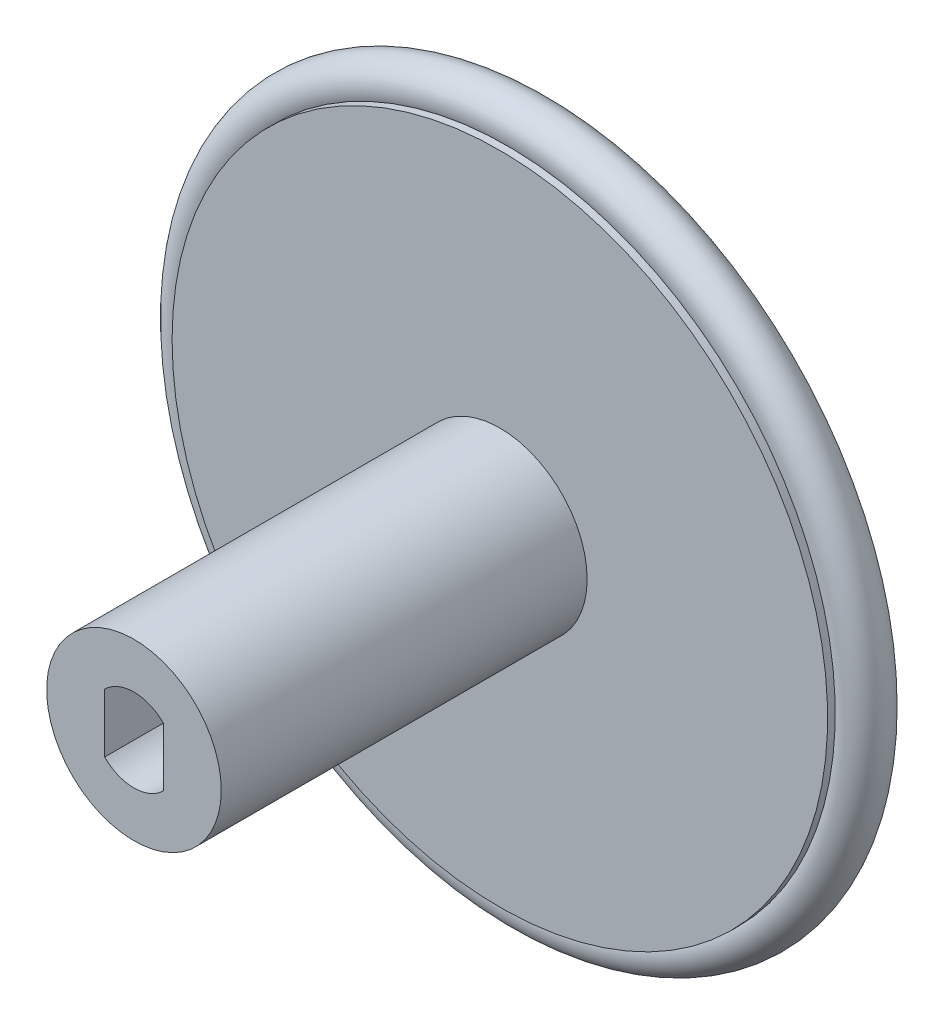
SolidWorks part; units mm, degrees
ref_plane "Alzado" through (0, 0, 0) normal (0, 0, 1) x (1, 0, 0)
ref_plane "Planta" through (0, 0, 0) normal (0, 1, 0) x (1, 0, 0)
ref_plane "Vista lateral" through (0, 0, 0) normal (1, 0, 0) x (0, 0, -1)
sketch "Croquis1" plane through (0, 0, 0) normal (1, 0, 0) x (0, 0, -1)
  line L0 (6.2271, 0) -> (-6.2271, 0) construction
  line L1 (0, 21.5) -> (0, -21.5) construction
  line L2 (-1.9, 0) -> (-1.9, 21.5)
  line L3 (-1.9, 21.5) -> (-1.4, 21.5)
  line L4 (-1.4, 21.5) -> (-0.5, 19.0002)
  line L5 (-0.5, 19.0002) -> (0.5, 19.0002)
  line L6 (1.4, 21.5) -> (0.5, 19.0002)
  line L7 (1.9, 21.5) -> (1.4, 21.5)
  line L8 (1.9, 0) -> (1.9, 21.5)
  line L9 (-1.9, 0) -> (1.9, 0)
  point P4 (0, 0)
  point P8 (0, 0)
  point P18 (0, 19.0002)
  dimension "D1" = 43
  dimension "D2" = 3.8
  dimension "D3" = 19.8
  dimension "D4" = 1
  dimension "D5" = 0.5
  dimension "D6" = 2.6569
revolve "Revolución1" add sketch "Croquis1" angle 360 about L0
sketch "Croquis3" plane through (0, 0, 1.9) normal (0, 0, 1) x (1, 0, 0)
  line L1 (-1.925, 1.9287) -> (1.925, 1.9287) construction
  line L2 (-1.925, 1.9287) -> (-1.925, -1.9287)
  line L3 (-1.925, -1.9287) -> (1.925, -1.9287) construction
  line L4 (1.925, 1.9287) -> (1.925, -1.9287)
  line L5 (-1.925, 1.9287) -> (1.925, -1.9287) construction
  line L6 (-1.925, -1.9287) -> (1.925, 1.9287) construction
  circle A0 centre (0, 0) radius 2.725 construction
  arc A1 (-1.925, 1.9287) -> (1.925, 1.9287) centre (0, 0) cw
  arc A2 (-1.925, -1.9287) -> (1.925, -1.9287) centre (0, 0) ccw
  circle A3 centre (0, 0) radius 5.725
  dimension "D1" = 5.45
  dimension "D4" = 11.45
  dimension "D2" = 3.85
  dimension "D3" = 3
extrude "Saliente-Extruir2" add sketch "Croquis3" along normal blind 24
sketch "Croquis4" plane through (0, 0, 25.9) normal (0, 0, 1) x (1, 0, 0)
  line L2 (-1.925, 1.9287) -> (-1.925, -1.9287)
  line L3 (1.925, -1.9287) -> (1.925, 1.9287)
  line L4 (-1.925, 1.9287) -> (-1.925, -1.9287)
  line L5 (1.925, -1.9287) -> (1.925, 1.9287)
  arc A2 (-1.925, -1.9287) -> (1.925, -1.9287) centre (0, 0) ccw
  arc A3 (1.925, 1.9287) -> (-1.925, 1.9287) centre (0, 0) ccw
  arc A4 (-1.925, -1.9287) -> (1.925, -1.9287) centre (0, 0) ccw
  arc A5 (1.925, 1.9287) -> (-1.925, 1.9287) centre (0, 0) ccw
  dimension "D1" = 0
extrude "Saliente-Extruir3" add sketch "Croquis4" against normal up to next from offset 5 offset against normal yes
sketch "Croquis5" plane through (0, 0, 0) normal (1, 0, 0) x (0, 0, -1)
  line L0 (-0.5, 19.0002) -> (-1.4, 21.5) construction
  line L1 (-9.0932, 0) -> (9.0932, 0) construction
  circle A0 centre (0, 22.0396) radius 1.5
  point P9 (0, 0)
  dimension "D1" = 3
revolve "Revolución2" add sketch "Croquis5" angle 360 about L1
